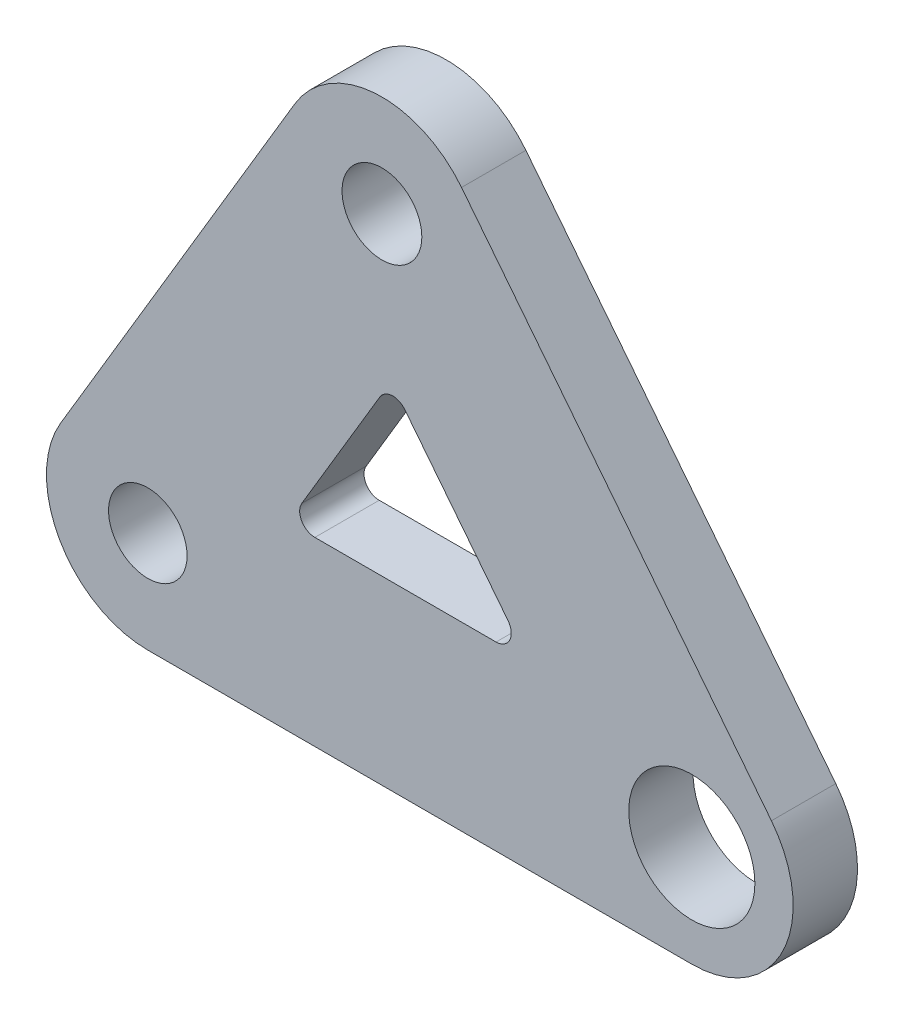
SolidWorks part; units mm, degrees
material "Balsa"
ref_plane "Front Plane" through (0, 0, 0) normal (0, 0, 1) x (1, 0, 0)
ref_plane "Top Plane" through (0, 0, 0) normal (0, 1, 0) x (1, 0, 0)
ref_plane "Right Plane" through (0, 0, 0) normal (1, 0, 0) x (0, 0, -1)
sketch "Sketch1" plane through (0, 0, 0) normal (0, 0, 1) x (1, 0, 0)
  line L0 (0, 0) -> (-23.1039, -38.8306) construction
  line L1 (-23.1039, -38.8306) -> (30.5799, -38.8306) construction
  line L2 (30.5799, -38.8306) -> (0, 0) construction
  line L6 (0.9059, -13.8786) -> (-9.2548, -30.9556)
  line L7 (-9.2548, -30.9556) -> (14.3543, -30.9556)
  line L8 (14.3543, -30.9556) -> (0.9059, -13.8786)
  line L9 (-31.6978, -33.7173) -> (-8.5939, 5.1133)
  line L10 (7.8563, 6.187) -> (38.4362, -32.6436)
  line L11 (-23.1039, -48.8306) -> (30.5799, -48.8306)
  circle A0 centre (0, 0) radius 3.9375
  circle A1 centre (-23.1039, -38.8306) radius 3.875
  circle A2 centre (30.5799, -38.8306) radius 6.223
  circle A6 centre (0, 0) radius 10
  circle A7 centre (30.5799, -38.8306) radius 10
  circle A8 centre (-23.1039, -38.8306) radius 10
  dimension "D2" = 7.75
  dimension "D3" = 12.446
  dimension "D6" = 53.6839
  dimension "D9" = 10
  dimension "D10" = 10
  dimension "D11" = 10
  dimension "D12" = 7.875
  dimension "D4" = 20
  dimension "D7" = 45.1841
  dimension "D8" = 49.4261
  dimension "D5" = 7.875
extrude "Boss-Extrude1" add sketch "Sketch1" along normal blind 6.35 contours A8 L11 A7 L10 A6 L9 L8 L7 L6 | A8 A1 | A6 A0 | A7 A2
fillet "Fillet1" radius 1.5 3 edges at (14.3543, -30.9556, 3.175) (0.9059, -13.8786, 3.175) (-9.2548, -30.9556, 3.175)
